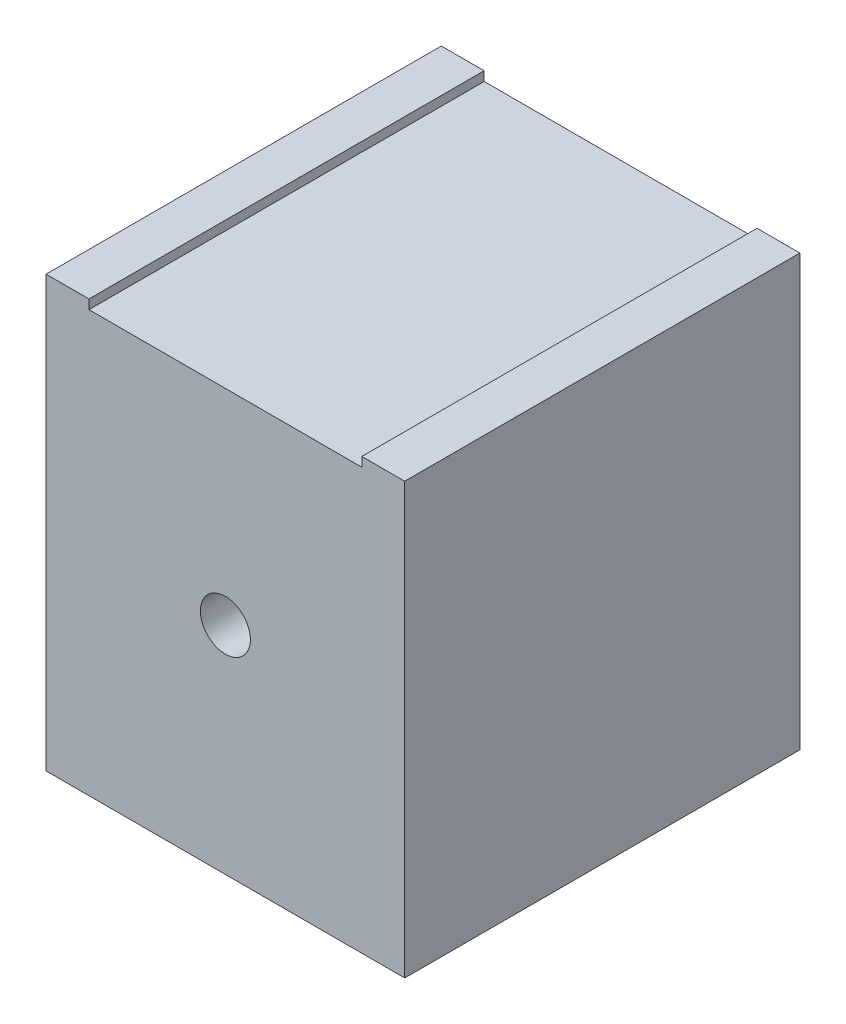
SolidWorks part; units mm, degrees
ref_plane "Front Plane" through (0, 0, 0) normal (0, 0, 1) x (1, 0, 0)
ref_plane "Top Plane" through (0, 0, 0) normal (0, 1, 0) x (1, 0, 0)
ref_plane "Right Plane" through (0, 0, 0) normal (1, 0, 0) x (0, 0, -1)
sketch "Sketch1" plane through (0, 0, 0) normal (0, 0, 1) x (1, 0, 0)
  line L1 (0, 0) -> (50.18, 0)
  line L2 (0, 0) -> (0, 60.2)
  line L3 (0, 60.2) -> (50.18, 60.2)
  line L4 (50.18, 0) -> (50.18, 60.2)
  dimension "D1" = 60.2
  dimension "D2" = 50.18
extrude "Boss-Extrude1" add sketch "Sketch1" along normal blind 55.3
sketch "Sketch2" plane through (0, 60.2, 0) normal (0, 1, 0) x (1, 0, 0)
  line L0 (50.18, 0) -> (0, 0) construction
  line L1 (6, 0) -> (44.18, 0)
  line L2 (6, 0) -> (6, -55.3)
  line L3 (6, -55.3) -> (44.18, -55.3)
  line L4 (44.18, 0) -> (44.18, -55.3)
  line L5 (50.18, -55.3) -> (0, -55.3) construction
  line L6 (0, -55.3) -> (0, 0) construction
  line L7 (50.18, -55.3) -> (50.18, 0) construction
  dimension "D1" = 6
  dimension "D2" = 6
extrude "Cut-Extrude1" cut sketch "Sketch2" against normal blind 1.3
sketch "Sketch4" plane through (0, 0, 55.3) normal (0, 0, 1) x (1, 0, 0)
  line L0 (25.09, 58.9) -> (25.09, 0) construction
  line L1 (6, 58.9) -> (44.18, 58.9) construction
  line L2 (0, 0) -> (50.18, 0) construction
hole_wizard "M8x1.0 Tapped Hole1" positions "Sketch5" profile "Sketch6" tap size "M8x1.0" standard "ANSI Metric"
sketch "Sketch5" plane through (0, 0, 55.3) normal (0, 0, 1) x (1, 0, 0)
  line L0 (25.09, 58.9) -> (25.09, 0) construction
  line L1 (6, 60.2) -> (0, 60.2) construction
  point P0 (25.09, 30.2)
  dimension "D1" = 30
sketch "Sketch6" plane through (25.09, 30.2, 55.3) normal (1, 0, 0) x (0, -1, 0)
  line L0 (0, 0) -> (0, 12.103)
  line L1 (0, 12.103) -> (3.5, 10)
  line L2 (3.5, 10) -> (3.5, 0)
  line L5 (3.5, 0) -> (0, 0)
  line L10 (0, 12.103) -> (-3.5, 10) construction
  line L11 (0, -6.35) -> (0, 107.95) construction
  dimension "Tap Drill Dia." = 7
  dimension "Tap Drill Depth" = 10
  dimension "Drill Angle" = 118
cosmetic thread "Hole Thread1" parameters "D1"=10, "D2"=8
